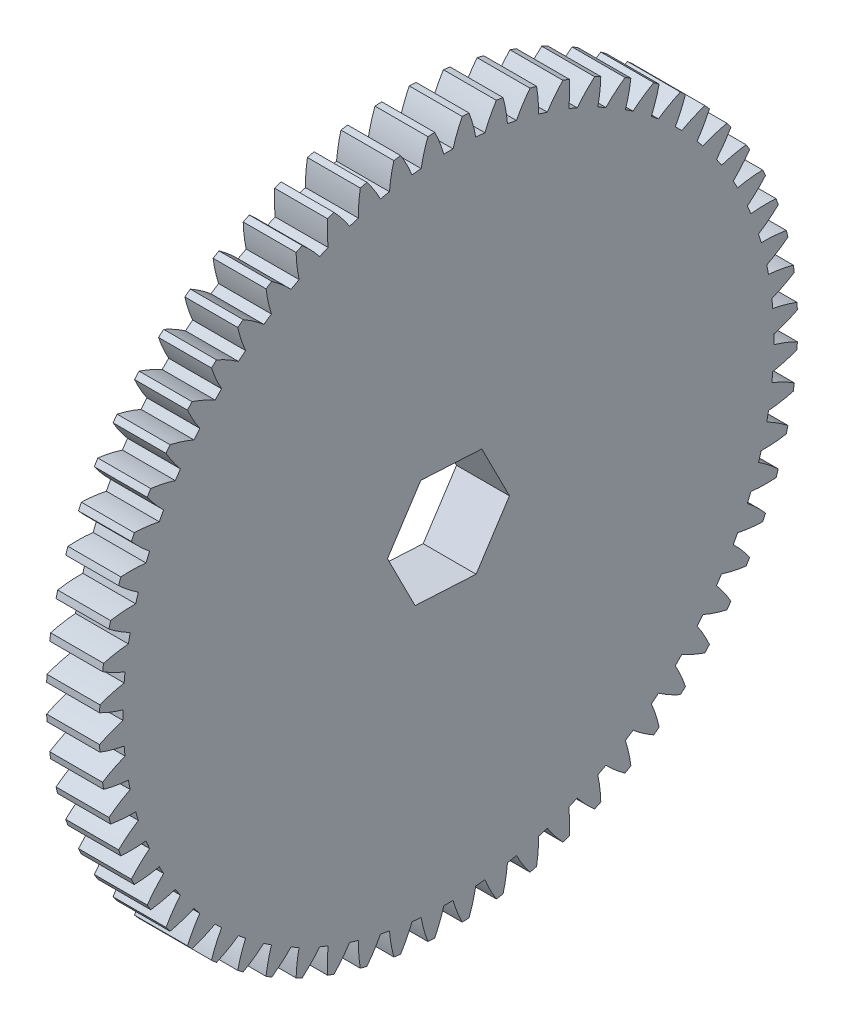
SolidWorks part; units mm, degrees
ref_plane "Plane1" through (0, 0, 0) normal (0, 0, 1) x (1, 0, 0)
ref_plane "Plane2" through (0, 0, 0) normal (0, 1, 0) x (1, 0, 0)
ref_plane "Plane3" through (0, 0, 0) normal (1, 0, 0) x (0, 0, -1)
other "Configuration Table"
sketch "HoldingSke" plane through (0, 0, 0) normal (0, 1, 0) x (1, 0, 0)
  line L0 (0, 0) -> (222.6925, -456.5874)
  line L1 (-15, 0) -> (100, 0) construction
  line L2 (0, 0) -> (-2.1039, 2.3779)
  line L3 (0, 0) -> (-11.863, 4.5341)
  line L4 (0, 0) -> (3.7858, 7.762)
  line L5 (0, 0) -> (-47.5972, -17.7524)
  line L6 (0, 0) -> (-5.2639, -3.5516)
  line L7 (-2.1039, 2.3779) -> (8.8308, 51.9871)
  line L8 (-76.2, 54.61) -> (-61.976, 54.61)
  line L9 (-71.009, 38.7566) -> (-53.1078, 45.2721)
  line L10 (-76.2, 71.12) -> (104.1128, 71.12)
  line L11 (0, 0) -> (-6.35, 0)
  line L12 (-76.2, 101.6) -> (-76.1492, 101.6)
  line L13 (24.9733, 27.94) -> (52.9518, 28.4284)
  line L14 (24.9733, 27.94) -> (25.0241, 27.9398)
  line L15 (24.9733, 27.94) -> (100.4021, 29.52)
  circle A0 centre (0, 0) radius 6.35
  circle A1 centre (0, 0) radius 1.27
  circle A2 centre (0, 0) radius 1.27
  circle A3 centre (0, 0) radius 6.35
  dimension "MHD" = 2.54
  dimension "Hub_dia" = 2.54
  dimension "Bore" = 12.7
  dimension "MBD" = 12.7
  dimension "Num_teeth" = 64
  dimension "Pitch" = 508
  dimension "Overall_len" = 50.8
  dimension "Show_teeth" = 64
  dimension "Thickness" = 6.35
  dimension "OAL" = 50.8001
  dimension "T_dim" = 14.224
  dimension "Ap" = 20
  dimension "H" = 19.05
  dimension "Pitch_radius" = 180.3128
  dimension "Width" = 6.35
  dimension "Backlash" = 0.0508
  dimension "Addendum_fac" = 1
  dimension "Dedendum_fac" = 1.2
  dimension "Clearance_fac" = 0.2
  dimension "Dedendum_add" = 0.0508
sketch "BasProSke" plane through (0, 0, 0) normal (0, 1, 0) x (1, 0, 0)
  line L0 (-10, 0) -> (60, 0) construction
  line L1 (0, 0) -> (0, 41.91)
  line L2 (0, 0) -> (6.35, 0)
  line L3 (6.35, 0) -> (6.35, 41.91)
  line L4 (6.35, 41.91) -> (0, 41.91)
  dimension "Thickness" = 6.35
  dimension "Diameter" = 83.82
revolve "Base-Revolve" add sketch "BasProSke" angle 360 about L0
sketch "TooCutSke" plane through (0, 0, 0) normal (1, 0, 0) x (0, 0, -1)
  line L1 (0, 0) -> (0, 107) construction
  line L2 (0, 0) -> (-1.0863, 40.6255) construction
  line L3 (0, 0) -> (-3.9872, 81.1618) construction
  line L4 (-1.0863, 40.6255) -> (-1.9936, 40.5809) construction
  arc A0 (0.5515, 39.0613) -> (-0.5515, 39.0613) centre (0, 0) ccw
  arc A1 (1.6617, 41.9025) -> (-1.6617, 41.9025) centre (0, 0) ccw
  circle A2 centre (0, 0) radius 40.64 construction
  circle A3 centre (0, 0) radius 38.1891 construction
  arc A4 (-0.5515, 39.0613) -> (-1.6617, 41.9025) centre (-16.181, 34.5917) ccw
  arc A5 (1.6617, 41.9025) -> (0.5515, 39.0613) centre (16.181, 34.5917) ccw
  dimension "Root_dia" = 78.1304
  dimension "Overcut_dia" = 83.8708
  dimension "Pitch_dia" = 81.28
  dimension "Base_dia" = 76.3782
  dimension "Flank_rad" = 16.256
  dimension "Half_ang" = 2.813
  dimension "Half_CT" = 0.9085
extrude "ToothCut" cut sketch "TooCutSke" along normal through all
fillet "Breaks" [suppressed] radius 0.0254
fillet "RootFillets" [suppressed] radius 0.3048
pattern_circular "TeethCuts" count 64 every 5.625 about axis through (-10, 0, 0) along (1, 0, 0) of "ToothCut", "RootFillets", "Breaks"
sketch "HubNeaOneSke" plane through (0, 0, 0) normal (-1, 0, 0) x (0, 0, 1)
  circle A0 centre (0, 0) radius 1.27
  dimension "Diameter" = 2.54
extrude "HubNearOne" [suppressed] add sketch "HubNeaOneSke" along normal blind 44.4501
sketch "HubNeaBotSke" plane through (0, 0, 0) normal (-1, 0, 0) x (0, 0, 1)
  circle A0 centre (0, 0) radius 1.27
  dimension "Diameter" = 2.54
extrude "HubNearBoth" add sketch "HubNeaBotSke" along normal blind 22.225
ref_plane "FarPln" through (6.35, 0, 0) normal (1, 0, 0) x (0, 0, -1)
sketch "HubFarSke" plane through (6.35, 0, 0) normal (1, 0, 0) x (0, 0, -1)
  circle A0 centre (0, 0) radius 1.27
  dimension "Diameter" = 2.54
extrude "HubFar" add sketch "HubFarSke" along normal blind 22.225
sketch "BorSke" plane through (0, 0, 0) normal (1, 0, 0) x (0, 0, -1)
  circle A0 centre (0, 0) radius 6.35
  dimension "Diameter" = 12.7
extrude "Bore" cut sketch "BorSke" along normal mid plane 101.6001
sketch "KeySke" plane through (0, 0, 0) normal (1, 0, 0) x (0, 0, -1)
  line L0 (-1.5875, 0) -> (-1.5875, 7.874)
  line L1 (-1.5875, 7.874) -> (1.5875, 7.874)
  line L2 (1.5875, 7.874) -> (1.5875, 0)
  line L3 (0, 0) -> (0, 34) construction
  line L4 (-1.5875, 0) -> (1.5875, 0)
  dimension "Offset" = 7.874
  dimension "Width" = 3.175
extrude "Keyway" [suppressed] cut sketch "KeySke" along normal mid plane 101.6001
pattern_circular "Keyway2" [suppressed] count 2 every 90 about axis through (-10, 0, 0) along (1, 0, 0)
sketch "Sketch1" plane through (6.35, 0, 0) normal (1, 0, 0) x (0, 0, -1)
  line L1 (4.0038, 6.1427) -> (-3.3179, 6.5387)
  line L2 (-3.3179, 6.5387) -> (-7.3216, 0.396)
  line L3 (-7.3216, 0.396) -> (-4.0038, -6.1427)
  line L4 (-4.0038, -6.1427) -> (3.3179, -6.5387)
  line L5 (3.3179, -6.5387) -> (7.3216, -0.396)
  line L6 (7.3216, -0.396) -> (4.0038, 6.1427)
  circle A0 centre (0, 0) radius 6.35 construction
  dimension "D1" = 12.7
extrude "Cut-Extrude1" cut sketch "Sketch1" against normal through all
equation "' \"Pitch@HoldingSke\" = 4"
equation "' \"Num_teeth@HoldingSke\" = 12"
equation "' \"Ap@HoldingSke\" =  20"
equation "' \"Ap@HoldingSke\" = 20"
equation "' \"Width@HoldingSke\" = 0.5"
equation "' \"Hub_dia@HoldingSke\"= 1"
equation "' \"Hub_dia@HoldingSke\" = 1"
equation "' \"Overall_len@HoldingSke\" = 1.0"
equation "' \"Bore@HoldingSke\" = 0.75"
equation "' \"T_dim@HoldingSke\" = 0.85"
equation "' \"Width@KeySke\" = 0.25"
equation "' \"Show_teeth@HoldingSke\" = 13"
equation "' \"Backlash@HoldingSke\" = 0.009"
equation "' \"Addendum_fac@HoldingSke\" = 1.0"
equation "' \"Dedendum_fac@HoldingSke\" = 1.25"
equation "' \"Dedendum_add@HoldingSke\" = 0.00005"
equation "' \"Clearance_fac@HoldingSke\" = 0.25"
equation "' \"Pitch@HoldingSke\" = 0.5"
equation "' \"Num_teeth@HoldingSke\" = 23"
equation "' \"Show_teeth@HoldingSke\" = 23"
equation "' \"Backlash@HoldingSke\" = 0.0375"
equation "\"Overcut_dia@TooCutSke\" = (\"Num_teeth@HoldingSke\" + 2 * \"Addendum_fac@HoldingSke\") / \"Pitch@HoldingSke\" + 0.002"
equation "\"Pitch_dia@TooCutSke\" = \"Num_teeth@HoldingSke\" / \"Pitch@HoldingSke\""
equation "\"Base_dia@TooCutSke\" = \"Num_teeth@HoldingSke\" / \"Pitch@HoldingSke\" * cos((\"Ap@HoldingSke\"  * 3.14159265 / 180))"
equation "\"Root_dia@TooCutSke\" = (\"Num_teeth@HoldingSke\" + 2) / \"Pitch@HoldingSke\" - 2 * (\"Addendum_fac@HoldingSke\" + \"Dedendum_fac@HoldingSke\") / \"Pitch@HoldingSke\" - \"Dedendum_add@HoldingSke\" * 2"
equation "\"Half_ang@TooCutSke\" = 180 / \"Num_teeth@HoldingSke\""
equation "\"Half_CT@TooCutSke\" = \"Num_teeth@HoldingSke\" / \"Pitch@HoldingSke\" * sin((3.14159265 / 2 / \"Num_teeth@HoldingSke\")) / 2 - 7 * \"Backlash@HoldingSke\" / 4"
equation "\"Flank_rad@TooCutSke\" = \"Num_teeth@HoldingSke\" / \"Pitch@HoldingSke\" / 5"
equation "\"Radius@RootFillets\" = \"Clearance_fac@HoldingSke\" / \"Pitch@HoldingSke\" + \"Dedendum_add@HoldingSke\""
equation "\"Break_rad@Breaks\" = 0.02 / \"Pitch@HoldingSke\""
equation "\"Thickness@HoldingSke\" = \"Width@HoldingSke\""
equation "\"OAL@HoldingSke\" = \"Thickness@HoldingSke\""
equation "\"MHD@HoldingSke\" = (\"Num_teeth@HoldingSke\" + 2) / \"Pitch@HoldingSke\" - 2 * (\"Addendum_fac@HoldingSke\" + \"Dedendum_fac@HoldingSke\")  / \"Pitch@HoldingSke\" - \"Dedendum_add@HoldingSke\" * 2"
equation "\"MBD@HoldingSke\" = (\"Num_teeth@HoldingSke\" + 2) / \"Pitch@HoldingSke\" - 2 * (\"Addendum_fac@HoldingSke\" + \"Dedendum_fac@HoldingSke\")  / \"Pitch@HoldingSke\" - \"Dedendum_add@HoldingSke\" * 2 - 0.002"
equation "\"MHD@HoldingSke\" = ((sgn( \"MHD@HoldingSke\" - \"Hub_dia@HoldingSke\" )-1)*( \"MHD@HoldingSke\" - \"Hub_dia@HoldingSke\" ))/-2+ \"Hub_dia@HoldingSke\""
equation "\"MBD@HoldingSke\" = ((sgn( \"MBD@HoldingSke\" - \"Bore@HoldingSke\" )-1)*( \"MBD@HoldingSke\" - \"Bore@HoldingSke\" ))/-2+ \"Bore@HoldingSke\""
equation "\"OAL@HoldingSke\" = ((sgn( \"OAL@HoldingSke\" - \"Overall_len@HoldingSke\" )+1)*( \"OAL@HoldingSke\" - \"Overall_len@HoldingSke\" ))/2 + \"Overall_len@HoldingSke\" + 0.000002"
equation "\"Num_teeth@TeethCuts\" = int( \"Show_teeth@HoldingSke\" ) + 1"
equation "\"Num_teeth@TeethCuts\" = ((sgn( \"Num_teeth@TeethCuts\" - \"Num_teeth@HoldingSke\" )-1)*( \"Num_teeth@TeethCuts\" - \"Num_teeth@HoldingSke\" ))/-2+ \"Num_teeth@HoldingSke\""
equation "\"Num_teeth@TeethCuts\" = ((sgn( \"Num_teeth@TeethCuts\" - 2.0)+1)*( \"Num_teeth@TeethCuts\" - 2.0))/2 +2.0"
equation "\"Angle@TeethCuts\" = 360.0 / \"Num_teeth@HoldingSke\""
equation "\"Diameter@BasProSke\" = (\"Num_teeth@HoldingSke\" + 2 * \"Addendum_fac@HoldingSke\") / \"Pitch@HoldingSke\""
equation "\"Thickness@BasProSke\"  = \"Thickness@HoldingSke\""
equation "' \"Fillet_rad@BasProSke\" =  \"Thickness@HoldingSke\" * 0.05"
equation "' \"Fillet_rad@BasProSke\" = \"Thickness@HoldingSke\" * 0.05"
equation "\"MHD@HoldingSke\" = ((sgn( \"MHD@HoldingSke\" - \"Root_dia@TooCutSke\" )-1)*( \"MHD@HoldingSke\" - \"Root_dia@TooCutSke\" ))/-2+ \"Root_dia@TooCutSke\""
equation "\"Diameter@HubNeaOneSke\" = \"MHD@HoldingSke\""
equation "\"Length@HubNearOne\" = \"OAL@HoldingSke\" - \"Thickness@BasProSke\""
equation "\"Diameter@HubNeaBotSke\" = \"MHD@HoldingSke\""
equation "\"Length@HubNearBoth\" = ( \"OAL@HoldingSke\" - \"Thickness@BasProSke\" ) / 2.0"
equation "\"Thickness@FarPln\" = \"Thickness@BasProSke\""
equation "\"Diameter@HubFarSke\" = \"MHD@HoldingSke\""
equation "\"Length@HubFar\" = ( \"OAL@HoldingSke\" - \"Thickness@BasProSke\" ) / 2.0"
equation "\"Diameter@BorSke\" = \"MBD@HoldingSke\""
equation "\"D1@Bore\" = \"OAL@HoldingSke\" * 2.0"
equation "\"D1@Keyway\" = \"OAL@HoldingSke\" * 2.0"
equation "\"Offset@KeySke\" = \"T_dim@HoldingSke\" - \"MBD@HoldingSke\" / 2.0"
